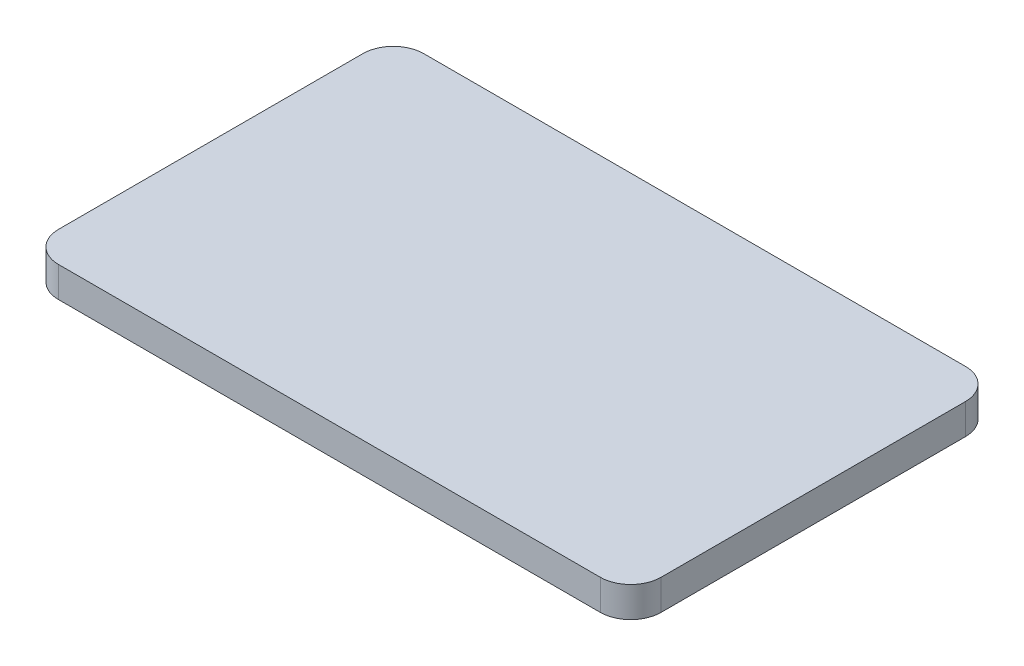
SolidWorks part; units mm, degrees
ref_plane "Front Plane" through (0, 0, 0) normal (0, 0, 1) x (1, 0, 0)
ref_plane "Top Plane" through (0, 0, 0) normal (0, 1, 0) x (1, 0, 0)
ref_plane "Right Plane" through (0, 0, 0) normal (1, 0, 0) x (0, 0, -1)
sketch "Sketch2" plane through (0, 0, 0) normal (0, 1, 0) x (1, 0, 0)
  line L0 (44.5, 30) -> (-44.5, 30)
  line L1 (49.5, 25) -> (49.5, -25)
  line L2 (44.5, -30) -> (-44.5, -30)
  line L3 (-49.5, 25) -> (-49.5, -25)
  arc A0 (49.5, -25) -> (44.5, -30) centre (44.5, -25) cw
  arc A1 (44.5, 30) -> (49.5, 25) centre (44.5, 25) cw
  arc A2 (-44.5, -30) -> (-49.5, -25) centre (-44.5, -25) cw
  arc A3 (-44.5, 30) -> (-49.5, 25) centre (-44.5, 25) ccw
extrude "Boss-Extrude1" add sketch "Sketch2" along normal blind 5
